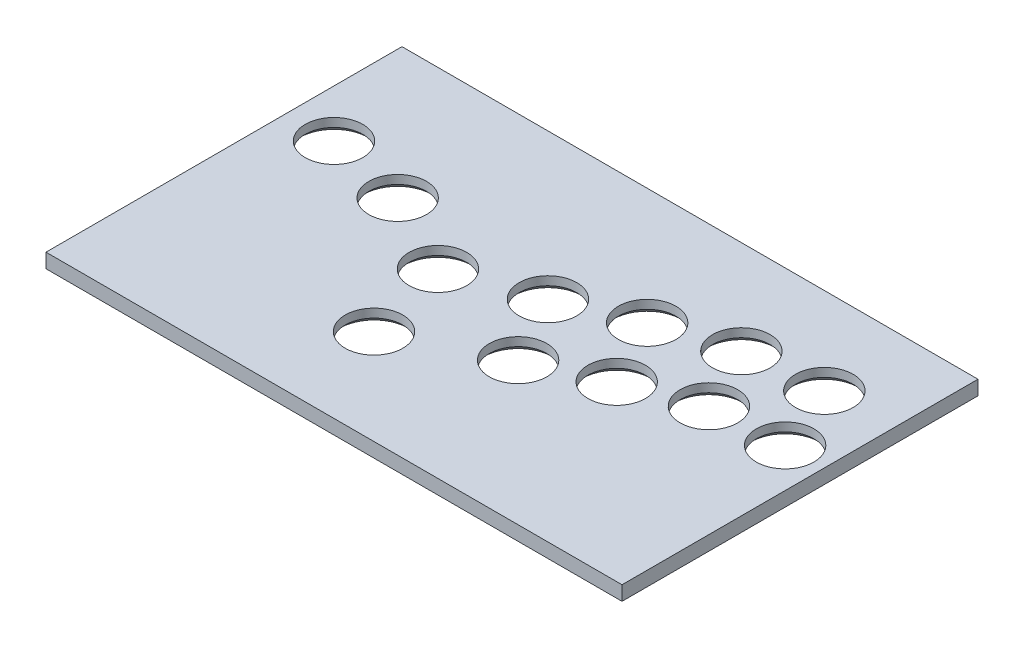
SolidWorks part; units mm, degrees
ref_plane "Front Plane" through (0, 0, 0) normal (0, 0, 1) x (1, 0, 0)
ref_plane "Top Plane" through (0, 0, 0) normal (0, 1, 0) x (1, 0, 0)
ref_plane "Right Plane" through (0, 0, 0) normal (1, 0, 0) x (0, 0, -1)
sketch "Sketch1" plane through (0, 0, 0) normal (0, 1, 0) x (1, 0, 0)
  line L5 (-111.3826, 24.1862) -> (88.6174, 24.1862)
  line L6 (-111.3826, 24.1862) -> (-111.3826, -99.4138)
  line L7 (-111.3826, -99.4138) -> (88.6174, -99.4138)
  line L8 (88.6174, 24.1862) -> (88.6174, -99.4138)
  circle A0 centre (-30.5462, -66.3515) radius 10
  circle A1 centre (-66.6325, -22.0572) radius 10
  circle A2 centre (-94.8237, -15.9794) radius 10
  circle A3 centre (-10.0903, -26.4253) radius 10
  circle A4 centre (65.4495, -6.0021) radius 10
  circle A5 centre (39.1205, -8.4764) radius 10
  circle A6 centre (3.0501, -49.9237) radius 10
  circle A7 centre (26.6846, -39.3297) radius 10
  circle A8 centre (50.0349, -30.6577) radius 10
  circle A9 centre (-38.2869, -36.4229) radius 10
  circle A10 centre (75.0408, -29.205) radius 10
  circle A11 centre (14.2288, -16.292) radius 10
  point P8 (-67.7498, -21.5967)
  point P29 (-66.6325, -22.0572)
  point P30 (-38.2869, -36.4229)
  dimension "D3" = 20
  dimension "D1" = 200
  dimension "D2" = 123.6
extrude "Boss-Extrude1" add sketch "Sketch1" along normal blind 5 contours L5 L8 L7 L6
chamfer "Chamfer1" distance 2 angle 45 12 edges at (-94.8237, 0, 25.9794) (-66.6325, 0, 32.0572) (-38.2869, 0, 46.4229) (-30.5462, 0, 76.3515) (3.0501, 0, 59.9237) (-10.0903, 0, 36.4253) (26.6846, 0, 49.3297) (14.2288, 0, 26.292) (50.0349, 0, 40.6577) (75.0408, 0, 39.205) (39.1205, 0, 18.4764) (65.4495, 0, 16.0021)
